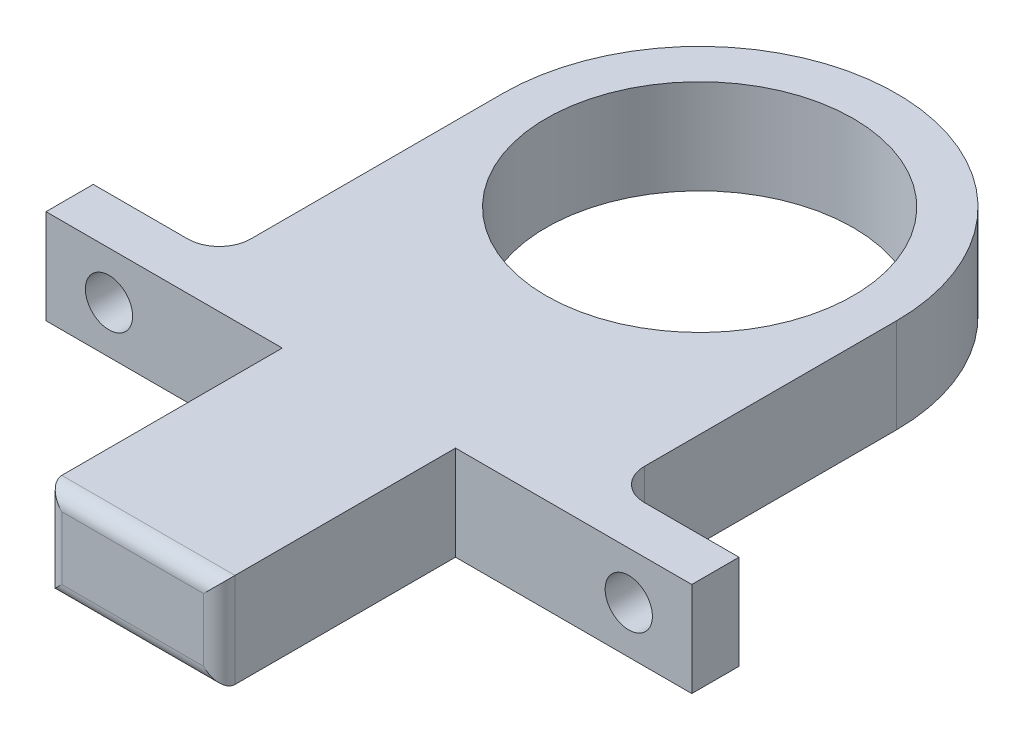
SolidWorks part; units mm, degrees
ref_plane "Alzado" through (0, 0, 0) normal (0, 0, 1) x (1, 0, 0)
ref_plane "Planta" through (0, 0, 0) normal (0, 1, 0) x (1, 0, 0)
ref_plane "Vista lateral" through (0, 0, 0) normal (1, 0, 0) x (0, 0, -1)
sketch "Croquis1" plane through (0, 0, 0) normal (0, 1, 0) x (1, 0, 0)
  line L0 (-12.5, 0) -> (12.5, 0) construction
  line L1 (-12.5, 0) -> (-12.5, -16)
  line L2 (-12.5, -21) -> (12.5, -21)
  line L3 (12.5, -16) -> (12.5, 0)
  line L4 (-20.5, -18) -> (20.5, -18) construction
  line L6 (-20.5, -18) -> (-14.5, -18)
  line L7 (-20.5, -18) -> (-20.5, -21)
  line L8 (-20.5, -21) -> (-12.5, -21)
  line L9 (-12.5, -14) -> (-12.5, -21)
  line L10 (20.5, -18) -> (14.5, -18)
  line L11 (20.5, -18) -> (20.5, -21)
  line L12 (20.5, -21) -> (12.5, -21)
  line L13 (12.5, -14) -> (12.5, -21)
  line L14 (-5.5, -21) -> (5.5, -21)
  line L15 (-5.5, -21) -> (-5.5, -36)
  line L16 (-5.5, -36) -> (5.5, -36)
  line L17 (5.5, -21) -> (5.5, -36)
  circle A0 centre (0, 0) radius 12.5
  circle A1 centre (0, 0) radius 9.75
  arc A2 (14.5, -18) -> (12.5, -16) centre (14.5, -16) cw
  arc A3 (-14.5, -18) -> (-12.5, -16) centre (-14.5, -16) ccw
  dimension "D1" = 25
  dimension "D2" = 19.5
  dimension "D6" = 2
  dimension "D3" = 21
  dimension "D4" = 3
  dimension "D5" = 8
  dimension "D7" = 8
  dimension "D8" = 25
  dimension "D9" = 12.5
  dimension "D10" = 11
  dimension "D11" = 15
  dimension "D12" = 5.5
extrude "Saliente-Extruir1" add sketch "Croquis1" along normal blind 6
sketch "Croquis2" plane through (0, 0, 21) normal (0, 0, 1) x (1, 0, 0)
  line L0 (-20.5, 3) -> (20.5, 3) construction
  line L1 (-20.5, 6) -> (-20.5, 0) construction
  line L2 (20.5, 6) -> (20.5, 0) construction
  circle A0 centre (-16.5, 3) radius 1.5
  circle A1 centre (16.5, 3) radius 1.5
  dimension "D3" = 3
  dimension "D4" = 3
  dimension "D1" = 4
  dimension "D2" = 4
extrude "Cortar-Extruir1" cut sketch "Croquis2" against normal blind 6
sketch "Croquis3" plane through (0, 0, 18) normal (0, 0, -1) x (-1, 0, 0)
  circle A0 centre (-16.5, 3) radius 3
  circle A1 centre (16.5, 3) radius 3
  dimension "D1" = 6
  dimension "D2" = 6
extrude "Cortar-Extruir2" cut sketch "Croquis3" along normal blind 6
fillet "Redondeo1" radius 1 4 edges at (5.5, 3, 36) (-5.5, 3, 36) (0, 0, 36) (0, 6, 36)
